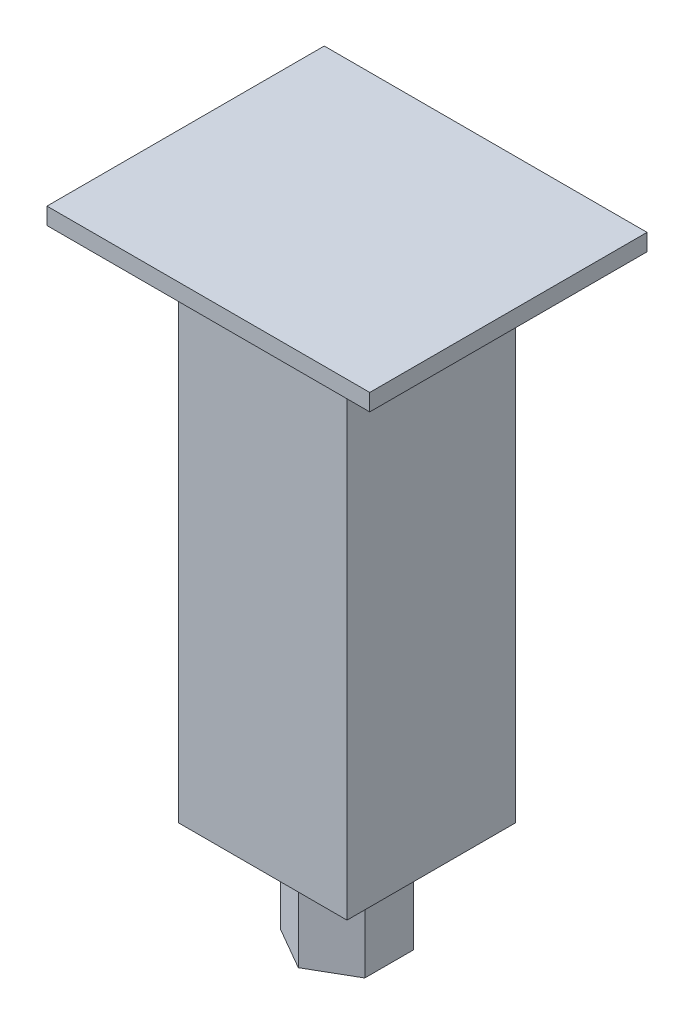
SolidWorks part; units mm, degrees
ref_plane "Front Plane" through (0, 0, 0) normal (0, 0, 1) x (1, 0, 0)
ref_plane "Top Plane" through (0, 0, 0) normal (0, 1, 0) x (1, 0, 0)
ref_plane "Right Plane" through (0, 0, 0) normal (1, 0, 0) x (0, 0, -1)
sketch "Sketch1" plane through (0, 0, 0) normal (0, 1, 0) x (1, 0, 0)
  line L1 (0, 5.7735) -> (-5, 2.8868)
  line L2 (-5, 2.8868) -> (-5, -2.8868)
  line L3 (-5, -2.8868) -> (0, -5.7735)
  line L4 (0, -5.7735) -> (5, -2.8868)
  line L5 (5, -2.8868) -> (5, 2.8868)
  line L6 (5, 2.8868) -> (0, 5.7735)
  circle A0 centre (0, 0) radius 5 construction
  point P10 (0, 0)
  dimension "D1" = 10
extrude "Boss-Extrude1" add sketch "Sketch1" along normal blind 12
sketch "Sketch2" plane through (0, 12, 0) normal (0, 1, 0) x (1, 0, 0)
  line L1 (-10, -10) -> (10, -10)
  line L2 (-10, -10) -> (-10, 10)
  line L3 (-10, 10) -> (10, 10)
  line L4 (10, -10) -> (10, 10)
  line L5 (-10, -10) -> (10, 10) construction
  line L6 (-10, 10) -> (10, -10) construction
  point P0 (0, 0)
  dimension "D1" = 20
  dimension "20" = 20
extrude "Boss-Extrude2" add sketch "Sketch2" along normal blind 60
sketch "Sketch3" plane through (0, 72, 0) normal (0, 1, 0) x (1, 0, 0)
  line L1 (-19.1421, -16.4444) -> (19.1421, -16.4444)
  line L2 (-19.1421, -16.4444) -> (-19.1421, 16.4444)
  line L3 (-19.1421, 16.4444) -> (19.1421, 16.4444)
  line L4 (19.1421, -16.4444) -> (19.1421, 16.4444)
  line L5 (-19.1421, -16.4444) -> (19.1421, 16.4444) construction
  line L6 (-19.1421, 16.4444) -> (19.1421, -16.4444) construction
  point P0 (0, 0)
extrude "Boss-Extrude3" add sketch "Sketch3" along normal blind 2
